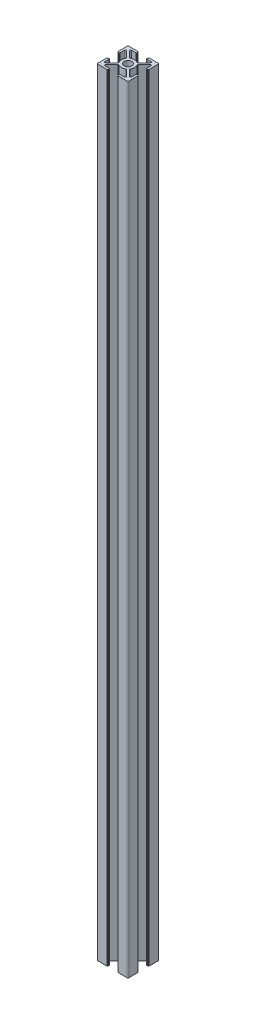
SolidWorks part; units mm, degrees
ref_plane "Front Plane" through (0, 0, 0) normal (0, 0, 1) x (1, 0, 0)
ref_plane "Top Plane" through (0, 0, 0) normal (0, 1, 0) x (1, 0, 0)
ref_plane "Right Plane" through (0, 0, 0) normal (1, 0, 0) x (0, 0, -1)
sketch "Sketch1" plane through (0, 0, 0) normal (0, 1, 0) x (1, 0, 0)
  point P0 (0, 0)
  line B0 (-6.2474, 8.6) -> (-3.6, 8.6)
  line B1 (-9.5, -10) -> (-3.6, -10)
  line B2 (-10, -9.5) -> (-10, -3.6)
  line B3 (-9.5, 10) -> (-3.6, 10)
  line B4 (10, -9.5) -> (10, -3.6)
  line B5 (-10, -10) -> (10, 10) construction
  line B6 (-10, 10) -> (10, -10) construction
  line B7 (8.6, -6.2474) -> (8.6, -3.6)
  line B8 (-6.2474, -8.6) -> (-3.6, -8.6)
  line B9 (-8.6, -6.2474) -> (-8.6, -3.6)
  line B10 (-7.7464, 6.7565) -> (-3.7448, 2.7548)
  line B11 (-6.6465, 7.6365) -> (-2.7548, 3.7448)
  line B12 (6.6465, 7.6365) -> (2.7548, 3.7448)
  line B13 (7.6365, 6.6465) -> (3.7448, 2.7548)
  line B14 (7.6365, -6.6465) -> (3.7448, -2.7548)
  line B15 (6.6465, -7.6365) -> (2.7548, -3.7448)
  line B16 (-6.6465, -7.6365) -> (-2.7548, -3.7448)
  line B17 (-7.6365, -6.6465) -> (-3.7448, -2.7548)
  line B18 (-3.4591, 2.4692) -> (-8.6, 7.6101) construction
  line B19 (-2.4692, 3.4591) -> (-7.6101, 8.6) construction
  line B20 (-8.6, 6.4029) -> (-8.6, 3.6)
  line B21 (8.6, -7.6101) -> (8.6, -3.2) construction
  line B22 (6.2474, -8.6) -> (3.6, -8.6)
  line B23 (-9, 3.2) -> (-9.6, 3.2)
  line B24 (-10, -3.2) -> (10, -3.2) construction
  line B25 (-10, 3.2) -> (10, 3.2) construction
  line B26 (-10, -3.2) -> (10, 3.2) construction
  line B27 (-9.6, -3.2) -> (-9, -3.2)
  line B28 (9, 3.2) -> (9.6, 3.2)
  line B29 (9, -3.2) -> (9.6, -3.2)
  line B30 (-10, 3.6) -> (-10, 9.5)
  line B31 (10, 3.6) -> (10, 9.5)
  line B32 (8.6, 3.6) -> (8.6, 6.2474)
  line B33 (-3.2, 9.6) -> (-3.2, 9)
  line B34 (-3.2, -10) -> (-3.2, 10) construction
  line B35 (3.2, -10) -> (3.2, 10) construction
  line B36 (-3.2, 10) -> (3.2, -10) construction
  line B37 (3.2, 9.6) -> (3.2, 9)
  line B38 (-3.2, -9.6) -> (-3.2, -9)
  line B39 (3.2, -9.6) -> (3.2, -9)
  line B40 (3.6, -10) -> (9.5, -10)
  line B41 (3.6, 10) -> (9.5, 10)
  line B42 (3.6, 8.6) -> (6.2474, 8.6)
  circle B43 centre (0, 0) radius 2.5
  arc B44 (-3.6669, 2.1485) -> (-3.6669, -2.1485) centre (0, 0) ccw
  arc B45 (2.1485, 3.6669) -> (-2.1485, 3.6669) centre (0, 0) ccw
  arc B46 (3.6669, -2.1485) -> (3.6669, 2.1485) centre (0, 0) ccw
  arc B47 (-2.1485, -3.6669) -> (2.1485, -3.6669) centre (0, 0) ccw
  arc B48 (-10, -9.5) -> (-9.5, -10) centre (-9.5, -9.5) ccw
  arc B49 (9.5, -10) -> (10, -9.5) centre (9.5, -9.5) ccw
  arc B50 (10, 9.5) -> (9.5, 10) centre (9.5, 9.5) ccw
  arc B51 (-9.5, 10) -> (-10, 9.5) centre (-9.5, 9.5) ccw
  arc B52 (-7.7464, 6.7565) -> (-8.6, 6.4029) centre (-8.1, 6.4029) ccw
  arc B53 (-6.2474, -8.6) -> (-6.6465, -7.6365) centre (-6.2474, -8.0356) cw
  arc B54 (-8.6, -6.2474) -> (-7.6365, -6.6465) centre (-8.0356, -6.2474) ccw
  arc B55 (6.2474, -8.6) -> (6.6465, -7.6365) centre (6.2474, -8.0356) ccw
  arc B56 (7.6365, -6.6465) -> (8.6, -6.2474) centre (8.0356, -6.2474) ccw
  arc B57 (8.6, 6.2474) -> (7.6365, 6.6465) centre (8.0356, 6.2474) ccw
  arc B58 (6.6465, 7.6365) -> (6.2474, 8.6) centre (6.2474, 8.0356) ccw
  arc B59 (-6.2474, 8.6) -> (-6.6465, 7.6365) centre (-6.2474, 8.0356) ccw
  arc B60 (2.7548, 3.7448) -> (2.1485, 3.6669) centre (2.4013, 4.0983) cw
  arc B61 (3.7448, 2.7548) -> (3.6669, 2.1485) centre (4.0983, 2.4013) ccw
  arc B62 (3.7448, -2.7548) -> (3.6669, -2.1485) centre (4.0983, -2.4013) cw
  arc B63 (2.7548, -3.7448) -> (2.1485, -3.6669) centre (2.4013, -4.0983) ccw
  arc B64 (-2.1485, -3.6669) -> (-2.7548, -3.7448) centre (-2.4013, -4.0983) ccw
  arc B65 (-3.7448, -2.7548) -> (-3.6669, -2.1485) centre (-4.0983, -2.4013) ccw
  arc B66 (-3.7448, 2.7548) -> (-3.6669, 2.1485) centre (-4.0983, 2.4013) cw
  arc B67 (-2.1485, 3.6669) -> (-2.7548, 3.7448) centre (-2.4013, 4.0983) cw
  arc B68 (-3.2, 9) -> (-3.6, 8.6) centre (-3.6, 9) cw
  arc B69 (-3.2, 9.6) -> (-3.6, 10) centre (-3.6, 9.6) ccw
  arc B70 (3.2, 9.6) -> (3.6, 10) centre (3.6, 9.6) cw
  arc B71 (3.2, 9) -> (3.6, 8.6) centre (3.6, 9) ccw
  arc B72 (9.6, 3.2) -> (10, 3.6) centre (9.6, 3.6) ccw
  arc B73 (9, 3.2) -> (8.6, 3.6) centre (9, 3.6) cw
  arc B74 (9.6, -3.2) -> (10, -3.6) centre (9.6, -3.6) cw
  arc B75 (9, -3.2) -> (8.6, -3.6) centre (9, -3.6) ccw
  arc B76 (3.2, -9) -> (3.6, -8.6) centre (3.6, -9) cw
  arc B77 (3.2, -9.6) -> (3.6, -10) centre (3.6, -9.6) ccw
  arc B78 (-3.2, -9.6) -> (-3.6, -10) centre (-3.6, -9.6) cw
  arc B79 (-3.2, -9) -> (-3.6, -8.6) centre (-3.6, -9) ccw
  arc B80 (-9, -3.2) -> (-8.6, -3.6) centre (-9, -3.6) cw
  arc B81 (-9.6, -3.2) -> (-10, -3.6) centre (-9.6, -3.6) ccw
  arc B82 (-9, 3.2) -> (-8.6, 3.6) centre (-9, 3.6) ccw
  arc B83 (-9.6, 3.2) -> (-10, 3.6) centre (-9.6, 3.6) cw
sketch_block_instance "2X2-1"
sketch_block "2X2" parameters "D4"=2.5, "D5"=4.25, "D10"=0.5, "D12"=0.5, "D13"=0.5644, "D14"=0.5, "D15"=0.4, "D1"=20, "D2"=1.4, "D3"=1.4, "D6"=6.4, "D7"=0.7, "D8"=1.4, "D9"=20, "D11"=6.4, "D16"=1.4
extrude "Boss-Extrude1" add sketch "Sketch1" along normal blind 500
